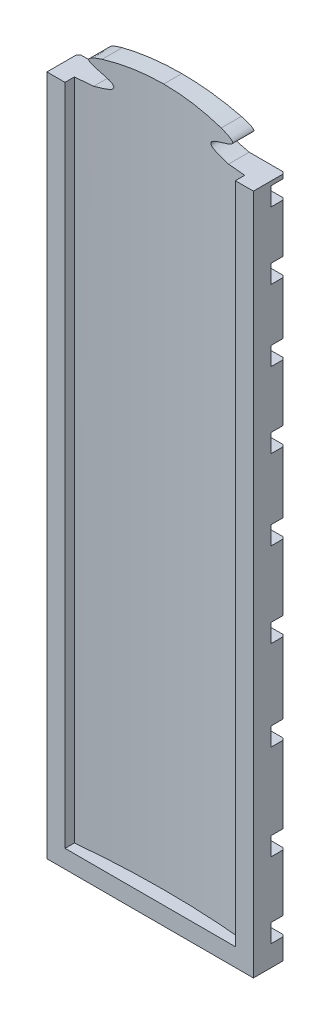
SolidWorks part; units mm, degrees
ref_plane "Front Plane" through (0, 0, 0) normal (0, 0, 1) x (1, 0, 0)
ref_plane "Top Plane" through (0, 0, 0) normal (0, 1, 0) x (1, 0, 0)
ref_plane "Right Plane" through (0, 0, 0) normal (1, 0, 0) x (0, 0, -1)
sketch "Sketch1" plane through (0, 0, 0) normal (0, 0, 1) x (1, 0, 0)
  line L0 (0, 464.91) -> (0, -53.7621) construction
  line L1 (207.2765, 0) -> (-181.268, 0) construction
  line L2 (23.8804, 464.91) -> (23.8804, -53.7621) construction
  line L3 (-23.8804, 464.91) -> (-23.8804, -53.7621) construction
  line L4 (16.5652, 464.91) -> (16.5652, -53.7621) construction
  line L5 (-16.5652, 464.91) -> (-16.5652, -53.7621) construction
  line L6 (-39.4637, 452.8091) -> (40.6786, 452.8091) construction
  line L7 (40.6786, 4) -> (-39.4637, 4) construction
  line L8 (-16.5652, 4) -> (-23.8804, 452.8091) construction
  line L9 (23.8804, 452.8091) -> (16.5652, 4) construction
  line L10 (-39.4637, 442.2134) -> (40.6786, 442.2134) construction
  line L11 (40.6786, 31.6398) -> (-39.4637, 31.6398) construction
  line L12 (40.6786, 430.9875) -> (-39.4637, 430.9875) construction
  line L13 (-39.4637, 455.3091) -> (40.6786, 455.3091)
  line L14 (-39.4637, 65.2793) -> (40.6786, 65.2793) construction
  line L15 (-39.4637, 364.0154) -> (40.6786, 364.0154) construction
  line L16 (-39.4637, 444.7134) -> (40.6786, 444.7134)
  line L17 (-39.4637, 61.2793) -> (40.6786, 61.2793)
  line L18 (-39.4637, 97.0308) -> (40.6786, 97.0308) construction
  line L19 (-39.4637, 93.0308) -> (40.6786, 93.0308)
  line L20 (40.6786, 127.0002) -> (-39.4637, 127.0002) construction
  line L21 (-39.4637, 67.7793) -> (40.6786, 67.7793)
  line L22 (-39.4637, 155.2875) -> (40.6786, 155.2875) construction
  line L23 (-39.4637, 366.5154) -> (40.6786, 366.5154)
  line L24 (40.6786, 181.9872) -> (-39.4637, 181.9872) construction
  line L25 (-39.4637, 99.5308) -> (40.6786, 99.5308)
  line L26 (-39.4637, 207.1884) -> (40.6786, 207.1884) construction
  line L27 (-39.4637, 151.2875) -> (40.6786, 151.2875)
  line L28 (40.6786, 230.9751) -> (-39.4637, 230.9751) construction
  line L29 (-39.4637, 157.7875) -> (40.6786, 157.7875)
  line L30 (-39.4637, 253.4267) -> (40.6786, 253.4267) construction
  line L31 (-39.4637, 203.1883) -> (40.6786, 203.1883)
  line L32 (40.6786, 274.6183) -> (-39.4637, 274.6183) construction
  line L33 (-39.4637, 209.6884) -> (40.6786, 209.6884)
  line L34 (-39.4637, 294.6205) -> (40.6786, 294.6205) construction
  line L35 (-39.4637, 249.4267) -> (40.6786, 249.4267)
  line L36 (40.6786, 313.5) -> (-39.4637, 313.5) construction
  line L37 (-39.4637, 255.9267) -> (40.6786, 255.9267)
  line L38 (-39.4637, 331.3199) -> (40.6786, 331.3199) construction
  line L39 (-39.4637, 290.6205) -> (40.6786, 290.6205)
  line L40 (40.6786, 348.1397) -> (-39.4637, 348.1397) construction
  line L41 (-39.4637, 297.1205) -> (40.6786, 297.1205)
  line L42 (-39.4637, 379.0001) -> (40.6786, 379.0001) construction
  line L43 (-39.4637, 327.3199) -> (40.6786, 327.3199)
  line L44 (40.6786, 393.1438) -> (-39.4637, 393.1437) construction
  line L45 (-39.4637, 333.8199) -> (40.6786, 333.8199)
  line L46 (-39.4637, 406.4936) -> (40.6786, 406.4936) construction
  line L47 (-39.4637, 360.0154) -> (40.6786, 360.0154)
  line L48 (40.6786, 419.0942) -> (-39.4637, 419.0942) construction
  line L49 (-39.4637, 381.5001) -> (40.6786, 381.5001)
  line L50 (-39.4637, 375.0001) -> (40.6786, 375.0001)
  line L51 (-39.4637, 408.9936) -> (40.6786, 408.9936)
  line L52 (-39.4637, 402.4936) -> (40.6786, 402.4936)
  line L53 (-39.4637, 438.2134) -> (40.6786, 438.2134)
  line L54 (-39.4637, 448.8091) -> (40.6786, 448.8091)
  line L55 (40.6786, 34.1398) -> (-39.4637, 34.1398)
  line L56 (40.6786, 433.4875) -> (-39.4637, 433.4875)
  line L57 (40.6786, 426.9875) -> (-39.4637, 426.9875)
  line L58 (40.6786, 415.0942) -> (-39.4637, 415.0942)
  line L59 (40.6786, 389.1438) -> (-39.4637, 389.1438)
  line L60 (40.6786, 129.5002) -> (-39.4637, 129.5002)
  line L61 (40.6786, 344.1397) -> (-39.4637, 344.1397)
  line L62 (40.6786, 184.4872) -> (-39.4637, 184.4872)
  line L63 (40.6786, 309.5) -> (-39.4637, 309.5)
  line L64 (40.6786, 233.4751) -> (-39.4637, 233.4751)
  line L65 (40.6786, 270.6183) -> (-39.4637, 270.6183)
  line L66 (40.6786, 277.1183) -> (-39.4637, 277.1183)
  line L67 (40.6786, 226.9751) -> (-39.4637, 226.9751)
  line L68 (40.6786, 316) -> (-39.4637, 316)
  line L69 (40.6786, 177.9872) -> (-39.4637, 177.9872)
  line L70 (40.6786, 350.6397) -> (-39.4637, 350.6397)
  line L71 (40.6786, 123.0002) -> (-39.4637, 123.0002)
  line L72 (40.6786, 395.6438) -> (-39.4637, 395.6438)
  line L73 (40.6786, 27.6398) -> (-39.4637, 27.6398)
  line L74 (40.6786, 421.5942) -> (-39.4637, 421.5942)
  line L75 (40.6786, 1) -> (-39.4637, 1)
  line L76 (40.6786, 7.5) -> (-39.4637, 7.5)
  line L77 (40.6786, 1) -> (40.6786, 7.5)
  line L78 (40.6786, 448.8091) -> (40.6786, 455.3091)
  line L79 (40.6786, 438.2134) -> (40.6786, 444.7134)
  line L80 (40.6786, 426.9875) -> (40.6786, 433.4875)
  line L81 (40.6786, 415.0942) -> (40.6786, 421.5942)
  line L82 (40.6786, 402.4936) -> (40.6786, 408.9936)
  line L83 (40.6786, 389.1438) -> (40.6786, 395.6438)
  line L84 (40.6786, 375.0001) -> (40.6786, 381.5001)
  line L85 (40.6786, 360.0154) -> (40.6786, 366.5154)
  line L86 (40.6786, 344.1397) -> (40.6786, 350.6397)
  line L87 (40.6786, 327.3199) -> (40.6786, 333.8199)
  line L88 (40.6786, 309.5) -> (40.6786, 316)
  line L89 (40.6786, 290.6205) -> (40.6786, 297.1205)
  line L90 (40.6786, 270.6183) -> (40.6786, 277.1183)
  line L91 (40.6786, 249.4267) -> (40.6786, 255.9267)
  line L92 (40.6786, 226.9751) -> (40.6786, 233.4751)
  line L93 (40.6786, 203.1883) -> (40.6786, 209.6884)
  line L94 (40.6786, 177.9872) -> (40.6786, 184.4872)
  line L95 (40.6786, 151.2875) -> (40.6786, 157.7875)
  line L96 (40.6786, 123.0002) -> (40.6786, 129.5002)
  line L97 (40.6786, 93.0308) -> (40.6786, 99.5308)
  line L98 (40.6786, 61.2793) -> (40.6786, 67.7793)
  line L99 (40.6786, 27.6398) -> (40.6786, 34.1398)
  line L100 (-39.4637, 1) -> (-39.4637, 7.5)
  line L101 (-39.4637, 448.8091) -> (-39.4637, 455.3091)
  line L102 (-39.4637, 438.2134) -> (-39.4637, 444.7134)
  line L103 (-39.4637, 426.9875) -> (-39.4637, 433.4875)
  line L104 (-39.4637, 415.0942) -> (-39.4637, 421.5942)
  line L105 (-39.4637, 402.4936) -> (-39.4637, 408.9936)
  line L106 (-39.4637, 389.1438) -> (-39.4637, 395.6438)
  line L107 (-39.4637, 375.0001) -> (-39.4637, 381.5001)
  line L108 (-39.4637, 360.0154) -> (-39.4637, 366.5154)
  line L109 (-39.4637, 344.1397) -> (-39.4637, 350.6397)
  line L110 (-39.4637, 327.3199) -> (-39.4637, 333.8199)
  line L111 (-39.4637, 309.5) -> (-39.4637, 316)
  line L112 (-39.4637, 290.6205) -> (-39.4637, 297.1205)
  line L113 (-39.4637, 270.6183) -> (-39.4637, 277.1183)
  line L114 (-39.4637, 249.4267) -> (-39.4637, 255.9267)
  line L115 (-39.4637, 226.9751) -> (-39.4637, 233.4751)
  line L116 (-39.4637, 203.1883) -> (-39.4637, 209.6884)
  line L117 (-39.4637, 177.9872) -> (-39.4637, 184.4872)
  line L118 (-39.4637, 151.2875) -> (-39.4637, 157.7875)
  line L119 (-39.4637, 123.0002) -> (-39.4637, 129.5002)
  line L120 (-39.4637, 93.0308) -> (-39.4637, 99.5308)
  line L121 (-39.4637, 61.2793) -> (-39.4637, 67.7793)
  line L122 (-39.4637, 27.6398) -> (-39.4637, 34.1398)
  dimension "D7" = 2.5
  dimension "D31" = 6.5
  dimension "D1" = 23.8804
  dimension "D2" = 23.8804
  dimension "D3" = 16.5652
  dimension "D4" = 16.5652
  dimension "D5" = 452.8091
  dimension "D6" = 4
  dimension "D9" = 6.5
  dimension "D10" = 31.6398
  dimension "D11" = 65.2793
  dimension "D12" = 97.0308
  dimension "D13" = 127.0002
  dimension "D14" = 155.2875
  dimension "D15" = 181.9872
  dimension "D16" = 207.1884
  dimension "D17" = 230.9751
  dimension "D18" = 253.4267
  dimension "D19" = 274.6183
  dimension "D20" = 294.6205
  dimension "D21" = 313.5
  dimension "D22" = 331.3199
  dimension "D23" = 348.1397
  dimension "D24" = 442.2134
  dimension "D25" = 430.9875
  dimension "D26" = 419.0942
  dimension "D27" = 406.4936
  dimension "D28" = 393.1438
  dimension "D29" = 379.0001
  dimension "D30" = 364.0154
  dimension "D33" = 6.5
  dimension "D8" = 2.5
  dimension "D32" = 3
sketch "Sketch2" plane through (0, 0, 0) normal (0, 0, 1) x (1, 0, 0)
  line L0 (30.163, 490.1178) -> (30.163, -68.1918) construction
  line L1 (-30.163, 490.1178) -> (-30.163, -68.1918) construction
  line L2 (0, 464.91) -> (0, -53.7621) construction
  line L3 (36.563, -68.1918) -> (36.563, 490.1178) construction
  line L4 (-36.563, 490.1178) -> (-36.563, -68.1918) construction
  line L5 (-36.563, 0) -> (36.563, 0)
  line L6 (207.2765, 0) -> (-181.268, 0) construction
  line L7 (36.563, 0) -> (36.563, 465.7035)
  line L8 (36.563, 465.7035) -> (-36.563, 465.7035)
  line L9 (-36.563, 465.7035) -> (-36.563, 0)
  dimension "D1" = 30.163
  dimension "D2" = 30.163
  dimension "D3" = 6.4
  dimension "D4" = 6.4
extrude "Boss-Extrude1" add sketch "Sketch2" along normal blind 12.8
sketch "Sketch3" plane through (0, 0, 0) normal (0, 1, 0) x (1, 0, 0)
  line L0 (38.7043, 0) -> (-38.1623, 0) construction
  line L1 (39.8582, -6.4) -> (-38.1623, -6.4) construction
  line L2 (-36.563, -12.8) -> (36.563, -12.8) construction
  line L3 (38.7043, -311.2) -> (0, -311.2) construction
  line L4 (30.163, -12.8) -> (30.163, -7.8961)
  line L5 (-30.163, -12.8) -> (-30.163, -7.8961)
  arc A0 (30.163, -7.8961) -> (-30.163, -7.8961) centre (0, -311.2) ccw
  dimension "D1" = 6.4
  dimension "D2" = 304.8
  dimension "D3" = 30.163
  dimension "D4" = 30.163
extrude "Cut-Extrude3" cut sketch "Sketch3" against normal through all and the other way through all flip side to cut
sketch "Sketch4" plane through (0, 0, 0) normal (0, 0, 1) x (1, 0, 0)
  line L1 (-36.563, 0) -> (36.563, 0)
  line L2 (-36.563, 0) -> (-36.563, -6.4)
  line L3 (-36.563, -6.4) -> (36.563, -6.4)
  line L4 (36.563, 0) -> (36.563, -6.4)
  dimension "D1" = 6.4
extrude "Boss-Extrude3" add sketch "Sketch4" along normal blind 12.8
ref_plane "Plane1" through (0, 0, 4) normal (0, 0, 1) x (1, 0, 0)
sketch "Sketch6" plane through (0, 0, 4) normal (0, 0, 1) x (1, 0, 0)
  line L4 (-23.9019, 235.1951) -> (-49.3974, 235.1951)
  line L26 (88.4047, 229.6) -> (-88.9547, 229.6) construction
  line L27 (-36.563, -6.4) -> (36.563, -6.4) construction
  line L28 (38.8194, 235.4451) -> (23.9282, 235.4451)
  line L29 (-23.9282, 235.4451) -> (-49.3974, 235.4451)
  line L36 (-43.0535, 233.9982) -> (-37.9136, 235.1951) construction
  line L37 (18.1118, 248.2421) -> (-43.0535, 248.2421) construction
  line L38 (38.8194, 235.1951) -> (23.9019, 235.1951)
  line L39 (0, 221.5497) -> (0, 263.5634) construction
  line L40 (38.8194, 234.9451) -> (23.8757, 234.9451)
  line L41 (-23.8757, 234.9451) -> (-49.3974, 234.9451)
  line L42 (38.8194, 234.9451) -> (38.8194, -11.0071)
  line L43 (38.8194, -11.0071) -> (-43.0535, -11.0071)
  line L44 (-43.0535, -11.0071) -> (-49.3974, 234.9451)
  spline S0 degree 2 poles (0, 247.3679) (-10.7842, 247.3592) (-21.1489, 244.7709) knots 0 0 0 1 1 1
  spline S1 degree 3 poles (-21.1489, 244.7709) (-37.3576, 240.3411) (-4.2165, 239.3715) (-23.9019, 235.1951) knots 0 0 0 0 1 1 1 1
  spline S2 degree 3 poles (21.1489, 244.7709) (37.3576, 240.3411) (4.2165, 239.3715) (23.9019, 235.1951) knots 0 0 0 0 1 1 1 1
  spline S3 degree 2 poles (0, 247.3679) (10.7842, 247.3592) (21.1489, 244.7709) knots 0 0 0 1 1 1
  spline S4 degree 1 poles (21.2121, 245.0128) (23.9282, 235.4451) knots 0 0 1 1 construction
  spline S5 degree 1 poles (0, 247.6179) (21.2121, 245.0128) knots 0 0 1 1 construction
  spline S6 degree 1 poles (0, 247.6179) (-21.2121, 245.0128) knots 0 0 1 1 construction
  spline S7 degree 1 poles (-21.2121, 245.0128) (-23.9282, 235.4451) knots 0 0 1 1 construction
  spline S8 degree 3 poles (23.9282, 235.4451) (23.6348, 235.5075) (23.0312, 235.6397) (21.9693, 235.8882) (20.8094, 236.1907) (19.6992, 236.5347) (18.5615, 236.9688) (17.9094, 237.3695) (17.6986, 237.6707) (17.6829, 237.7979) (17.739, 237.9582) (18.0148, 238.258) (18.7071, 238.6703) (19.903, 239.162) (21.7672, 239.8167) (23.7279, 240.4802) (25.2001, 241.2084) (25.8203, 241.7115) (26.0573, 242.2461) (25.9835, 242.8528) (25.4979, 243.3457) (24.6357, 243.835) (23.7639, 244.2108) (22.8283, 244.5374) (21.9574, 244.8043) (21.4557, 244.9462) (21.2121, 245.0128) knots -0.000055 -0.000055 -0.000055 -0.000055 0.015564 0.031183 0.062421 0.09366 0.124898 0.187374 0.218612 0.24985 0.281088 0.312326 0.374802 0.437278 0.499755 0.624707 0.687183 0.749659 0.780897 0.812135 0.874612 0.90585 0.937088 0.968326 0.983945 0.999564 0.999564 0.999564 0.999564
  spline S9 degree 2 poles (21.2121, 245.0128) (10.816, 247.6092) (0, 247.6179) knots -0.000009 -0.000009 -0.000009 1.000129 1.000129 1.000129
  spline S10 degree 2 poles (0, 247.6179) (-10.816, 247.6092) (-21.2121, 245.0128) knots -0.000009 -0.000009 -0.000009 1.000129 1.000129 1.000129
  spline S11 degree 3 poles (-21.2121, 245.0128) (-21.4557, 244.9462) (-21.9574, 244.8043) (-22.8283, 244.5374) (-23.7639, 244.2108) (-24.6357, 243.835) (-25.4979, 243.3457) (-25.9835, 242.8528) (-26.0573, 242.2461) (-25.8203, 241.7115) (-25.2001, 241.2084) (-23.7279, 240.4802) (-21.7672, 239.8167) (-19.903, 239.162) (-18.7071, 238.6703) (-18.0148, 238.258) (-17.739, 237.9582) (-17.6829, 237.7979) (-17.6986, 237.6707) (-17.9094, 237.3695) (-18.5615, 236.9688) (-19.6992, 236.5347) (-20.8094, 236.1907) (-21.9693, 235.8882) (-23.0312, 235.6397) (-23.6348, 235.5075) (-23.9282, 235.4451) knots -0.000055 -0.000055 -0.000055 -0.000055 0.015564 0.031183 0.062421 0.09366 0.124898 0.187374 0.218612 0.24985 0.312326 0.374802 0.499755 0.562231 0.624707 0.687183 0.718421 0.749659 0.780897 0.812135 0.874612 0.90585 0.937088 0.968326 0.983945 0.999564 0.999564 0.999564 0.999564
  spline S12 degree 1 poles (21.0857, 244.529) (23.8757, 234.9451) knots 0 0 1 1 construction
  spline S13 degree 1 poles (0, 247.1179) (21.0857, 244.529) knots 0 0 1 1 construction
  spline S14 degree 1 poles (0, 247.1179) (-21.0857, 244.529) knots 0 0 1 1 construction
  spline S15 degree 1 poles (-21.0857, 244.529) (-23.8757, 234.9451) knots 0 0 1 1 construction
  spline S16 degree 3 poles (23.8757, 234.9451) (23.5787, 235.0082) (22.9678, 235.1413) (21.8899, 235.3927) (20.708, 235.6996) (19.5654, 236.0516) (18.6696, 236.3915) (18.0001, 236.7235) (17.5327, 237.0576) (17.2381, 237.4209) (17.1559, 237.8621) (17.323, 238.2556) (17.723, 238.6714) (18.4869, 239.1197) (19.7184, 239.6272) (21.1286, 240.1222) (22.5715, 240.6172) (23.8953, 241.1217) (24.9459, 241.6374) (25.4407, 242.0735) (25.5382, 242.3329) (25.5244, 242.4959) (25.3759, 242.7409) (25.0138, 243.0449) (24.423, 243.3812) (23.5911, 243.7412) (22.6782, 244.0603) (21.822, 244.3229) (21.3261, 244.4633) (21.0857, 244.529) knots 0.000055 0.000055 0.000055 0.000055 0.015686 0.031317 0.062579 0.093841 0.125102 0.156364 0.187626 0.218888 0.25015 0.281412 0.312674 0.375197 0.437721 0.500245 0.562768 0.625292 0.687816 0.75034 0.781601 0.812863 0.844125 0.875387 0.906649 0.937911 0.969173 0.984804 1.000434 1.000434 1.000434 1.000434
  spline S17 degree 2 poles (21.0857, 244.529) (10.7523, 247.1092) (0, 247.1179) knots 0.000009 0.000009 0.000009 0.99987 0.99987 0.99987
  spline S18 degree 2 poles (0, 247.1179) (-10.7523, 247.1092) (-21.0857, 244.529) knots 0.000009 0.000009 0.000009 0.99987 0.99987 0.99987
  spline S19 degree 3 poles (-21.0857, 244.529) (-21.3261, 244.4633) (-21.822, 244.3229) (-22.6782, 244.0603) (-23.5911, 243.7412) (-24.423, 243.3812) (-25.0138, 243.0449) (-25.3759, 242.7409) (-25.5244, 242.4959) (-25.5382, 242.3329) (-25.4407, 242.0735) (-24.9459, 241.6374) (-23.8953, 241.1217) (-22.5715, 240.6172) (-21.1286, 240.1222) (-19.7184, 239.6272) (-18.4869, 239.1197) (-17.723, 238.6714) (-17.323, 238.2556) (-17.1559, 237.8621) (-17.2381, 237.4209) (-17.5327, 237.0576) (-18.0001, 236.7235) (-18.6696, 236.3915) (-19.5654, 236.0516) (-20.708, 235.6996) (-21.8899, 235.3927) (-22.9678, 235.1413) (-23.5787, 235.0082) (-23.8757, 234.9451) knots 0.000055 0.000055 0.000055 0.000055 0.015686 0.031317 0.062579 0.093841 0.125102 0.156364 0.187626 0.218888 0.25015 0.312674 0.375197 0.437721 0.500245 0.562768 0.625292 0.687816 0.719078 0.75034 0.781601 0.812863 0.844125 0.875387 0.906649 0.937911 0.969173 0.984804 1.000434 1.000434 1.000434 1.000434
  dimension "D1" = 236
  dimension "D2" = 0.25
  dimension "D3" = 0.25
chamfer "Chamfer5" distance 0.7 angle 45 4 edges at (0, 465.7035, 0) (-36.563, 229.6518, 0) (0, -6.4, 0) (36.563, 229.6518, 0)
extrude "Cut-Extrude4" cut sketch "Sketch1" along normal blind 5
ref_plane "Plane2" through (0, 0, 12.8) normal (0, 0, 1) x (1, 0, 0)
sketch "Sketch7" plane through (0, 0, 12.8) normal (0, 0, 1) x (1, 0, 0)
  line L1 (-36.563, 465.7035) -> (36.563, 465.7035)
  line L2 (-36.563, 465.7035) -> (-36.563, -6.4)
  line L3 (-36.563, -6.4) -> (36.563, -6.4)
  line L4 (36.563, 465.7035) -> (36.563, -6.4)
extrude "Cut-Extrude7" cut sketch "Sketch7" against normal blind 1.6
extrude "Cut-Extrude9" cut sketch "Sketch6" against normal through all and the other way through all flip side to cut contours L42 L43 L44 L41 S19 S18 S17 S16 L40
